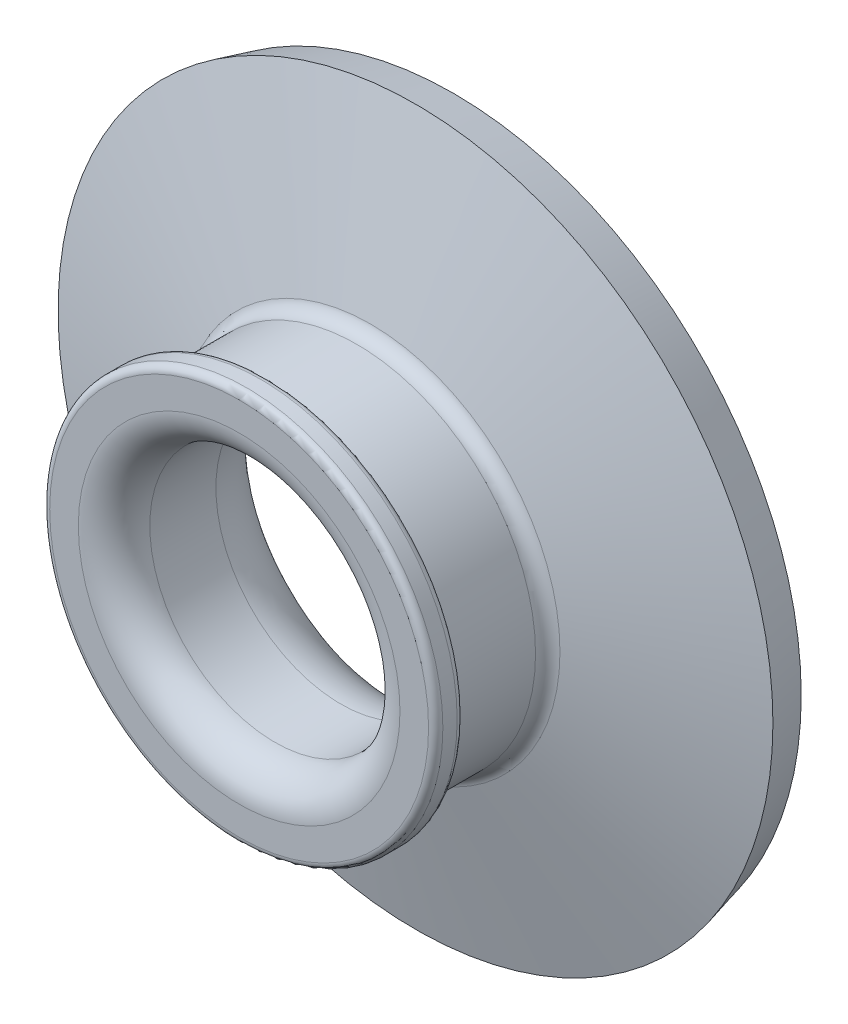
SolidWorks part; units mm, degrees
material "Nitrile Rubber"
ref_plane "Front Plane" through (0, 0, 0) normal (0, 0, 1) x (1, 0, 0)
ref_plane "Top Plane" through (0, 0, 0) normal (0, 1, 0) x (1, 0, 0)
ref_plane "Right Plane" through (0, 0, 0) normal (1, 0, 0) x (0, 0, -1)
sketch "Sketch1" plane through (0, 0, 0) normal (1, 0, 0) x (0, 0, -1)
  line L0 (0, 0) -> (95.2987, 0) construction
  line L1 (0, 26.5) -> (0, 22.5)
  line L2 (5, 17.5) -> (14.2449, 17.5)
  line L3 (23.9302, 25.0111) -> (30, 48.6311)
  line L4 (30, 48.6311) -> (24.6731, 50)
  line L5 (24.6731, 50) -> (18.3962, 26.4842)
  line L6 (16.4638, 25) -> (5, 25)
  line L7 (4, 26) -> (4, 26.5)
  line L8 (3, 27.5) -> (1, 27.5)
  arc A0 (4, 26.5) -> (3, 27.5) centre (3, 26.5) ccw
  arc A1 (1, 27.5) -> (0, 26.5) centre (1, 26.5) ccw
  arc A2 (5, 25) -> (4, 26) centre (5, 26) cw
  arc A3 (18.3962, 26.4842) -> (16.4638, 25) centre (16.4638, 27) cw
  arc A4 (14.2449, 17.5) -> (23.9302, 25.0111) centre (14.2449, 27.5) ccw
  arc A5 (0, 22.5) -> (5, 17.5) centre (5, 22.5) ccw
  point P19 (18, 25)
  point P22 (22, 17.5)
  dimension "D10" = 1
  dimension "D11" = 1
  dimension "D12" = 2
  dimension "D13" = 10
  dimension "D14" = 5
  dimension "D1" = 55
  dimension "D2" = 50
  dimension "D3" = 35
  dimension "D4" = 30
  dimension "D5" = 100
  dimension "D6" = 5.5
  dimension "D7" = 18
  dimension "D8" = 22
  dimension "D9" = 4
revolve "Revolve1" add sketch "Sketch1" angle 360 about L0
